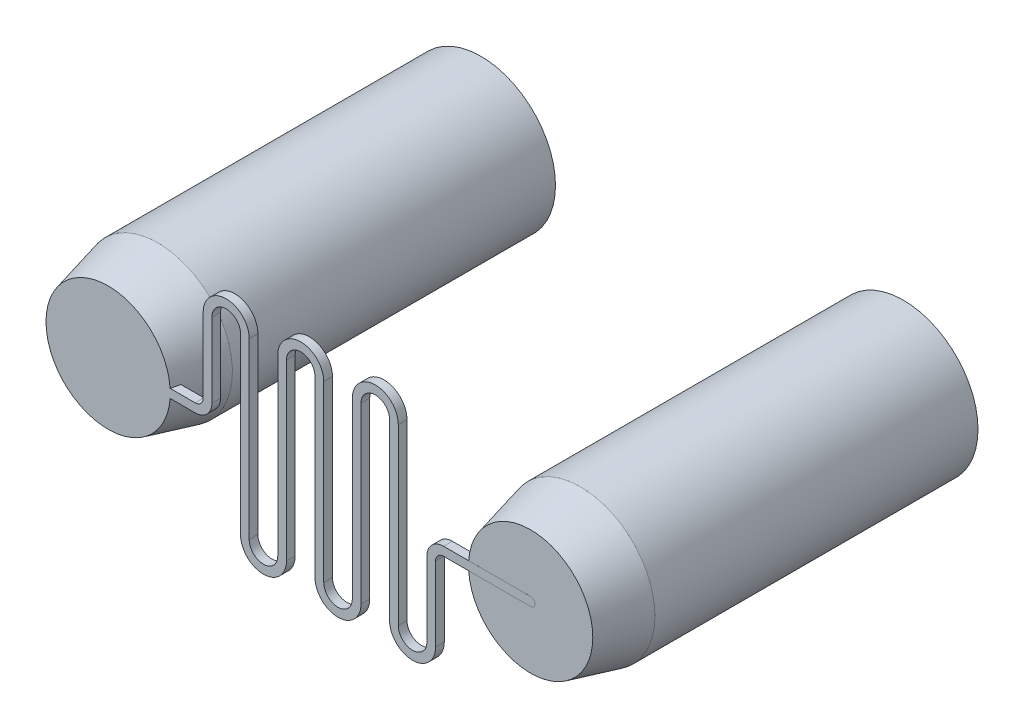
SolidWorks part; units mm, degrees
ref_plane "Front Plane" through (0, 0, 0) normal (0, 0, 1) x (1, 0, 0)
ref_plane "Top Plane" through (0, 0, 0) normal (0, 1, 0) x (1, 0, 0)
ref_plane "Right Plane" through (0, 0, 0) normal (1, 0, 0) x (0, 0, -1)
sketch "Sketch2" plane through (0, 0, 0) normal (0, 0, 1) x (1, 0, 0)
  line L3 (-20.5, -0.35) -> (-13.5, -0.35)
  line L6 (-12.15, 1) -> (-12.15, 7)
  line L9 (-9.85, 7) -> (-9.85, 0)
  line L12 (-9.85, 0) -> (-9.85, -7)
  line L15 (-6.15, -7) -> (-6.15, 0)
  line L18 (-6.15, 0) -> (-6.15, 7)
  line L21 (-3.85, 7) -> (-3.85, 0)
  line L22 (-3.85, 0) -> (-3.85, -7)
  line L23 (-0.15, -7) -> (-0.15, 0)
  line L24 (-0.15, 0) -> (-0.15, 7)
  line L25 (2.15, 7) -> (2.15, 0)
  line L26 (2.15, 0) -> (2.15, -7)
  line L27 (5.85, -7) -> (5.85, -1)
  line L28 (6.5, -0.35) -> (13.5, -0.35)
  line L29 (-20.5, 0.35) -> (-13.5, 0.35)
  line L30 (-12.85, 1) -> (-12.85, 7)
  line L31 (-9.15, 7) -> (-9.15, 0)
  line L32 (-9.15, 0) -> (-9.15, -7)
  line L33 (-6.85, -7) -> (-6.85, 0)
  line L34 (-6.85, 0) -> (-6.85, 7)
  line L35 (-3.15, 7) -> (-3.15, 0)
  line L36 (-3.15, 0) -> (-3.15, -7)
  line L37 (-0.85, -7) -> (-0.85, 0)
  line L38 (-0.85, 0) -> (-0.85, 7)
  line L39 (2.85, 7) -> (2.85, 0)
  line L40 (2.85, 0) -> (2.85, -7)
  line L41 (5.15, -7) -> (5.15, -1)
  line L42 (6.5, 0.35) -> (13.5, 0.35)
  arc A0 (13.5, -0.35) -> (13.5, 0.35) centre (13.5, 0) ccw
  arc A8 (-12.15, 1) -> (-13.5, -0.35) centre (-13.5, 1) cw
  arc A9 (-12.15, 7) -> (-9.85, 7) centre (-11, 7) cw
  arc A10 (-9.85, -7) -> (-6.15, -7) centre (-8, -7) ccw
  arc A11 (-6.15, 7) -> (-3.85, 7) centre (-5, 7) cw
  arc A12 (-3.85, -7) -> (-0.15, -7) centre (-2, -7) ccw
  arc A13 (-0.15, 7) -> (2.15, 7) centre (1, 7) cw
  arc A14 (2.15, -7) -> (5.85, -7) centre (4, -7) ccw
  arc A15 (5.85, -1) -> (6.5, -0.35) centre (6.5, -1) cw
  arc A16 (-12.85, 1) -> (-13.5, 0.35) centre (-13.5, 1) cw
  arc A17 (-12.85, 7) -> (-9.15, 7) centre (-11, 7) cw
  arc A18 (-9.15, -7) -> (-6.85, -7) centre (-8, -7) ccw
  arc A19 (-6.85, 7) -> (-3.15, 7) centre (-5, 7) cw
  arc A20 (-3.15, -7) -> (-0.85, -7) centre (-2, -7) ccw
  arc A21 (-0.85, 7) -> (2.85, 7) centre (1, 7) cw
  arc A22 (2.85, -7) -> (5.15, -7) centre (4, -7) ccw
  arc A23 (5.15, -1) -> (6.5, 0.35) centre (6.5, -1) cw
  arc A24 (-20.5, 0.35) -> (-20.5, -0.35) centre (-20.5, 0) ccw
  point P4 (0, 0)
  point P32 (5.5, 0)
  point P35 (-12.5, 0)
  dimension "D1" = 8
extrude "Boss-Extrude1" add sketch "Sketch2" along normal blind 0.7
ref_plane "Plane1" through (0, 0, 0) normal (0, 1, 0) x (1, 0, 0)
sketch "Sketch3" plane through (0, 0, 0) normal (0, 1, 0) x (1, 0, 0)
  line L0 (-20.5, -0.7) -> (-25.5, -0.7)
  line L2 (-20.5, -0.7) -> (-20.5, 29.3)
  line L3 (-20.5, 29.3) -> (-26.5, 29.3)
  line L4 (-26.5, 29.3) -> (-26.5, 3.3)
  line L5 (-26.5, 3.3) -> (-25.5, -0.7)
  dimension "D1" = 5
  dimension "D3" = 30
  dimension "D4" = 6
revolve "Revolve1" add sketch "Sketch3" angle 360 about L2
ref_plane "Plane2" through (0, 0, 0) normal (0, 1, 0) x (1, 0, 0)
sketch "Sketch4" plane through (0, 0, 0) normal (0, 1, 0) x (1, 0, 0)
  line L0 (13.5, -0.6996) -> (18.5, -0.6996)
  line L1 (13.5, -0.7) -> (13.5, 0) construction
  line L3 (13.5, -0.6996) -> (13.5, 29.3004)
  line L4 (13.5, 29.3004) -> (19.5, 29.3004)
  line L5 (19.5, 29.3004) -> (19.5, 3.3004)
  line L7 (19.5, 3.3004) -> (18.5, -0.6996)
  dimension "D1" = 5
  dimension "D3" = 30
  dimension "D4" = 6
revolve "Revolve2" add sketch "Sketch4" angle 360 about L3
sketch "Sketch5" plane through (0, 0, -29.3) normal (0, 0, -1) x (-1, 0, 0)
  circle A0 centre (-13.5, 0) radius 5
  circle A1 centre (20.5, 0) radius 5
  dimension "D1" = 10
  dimension "D2" = 10
extrude "Cut-Extrude1" cut sketch "Sketch5" against normal blind 27
sketch "Sketch6" plane through (0, 0, -29.3004) normal (0, 0, -1) x (-1, 0, 0)
  circle A0 centre (-13.5, 0) radius 5
  dimension "D1" = 10
extrude "Cut-Extrude2" cut sketch "Sketch6" against normal blind 27
